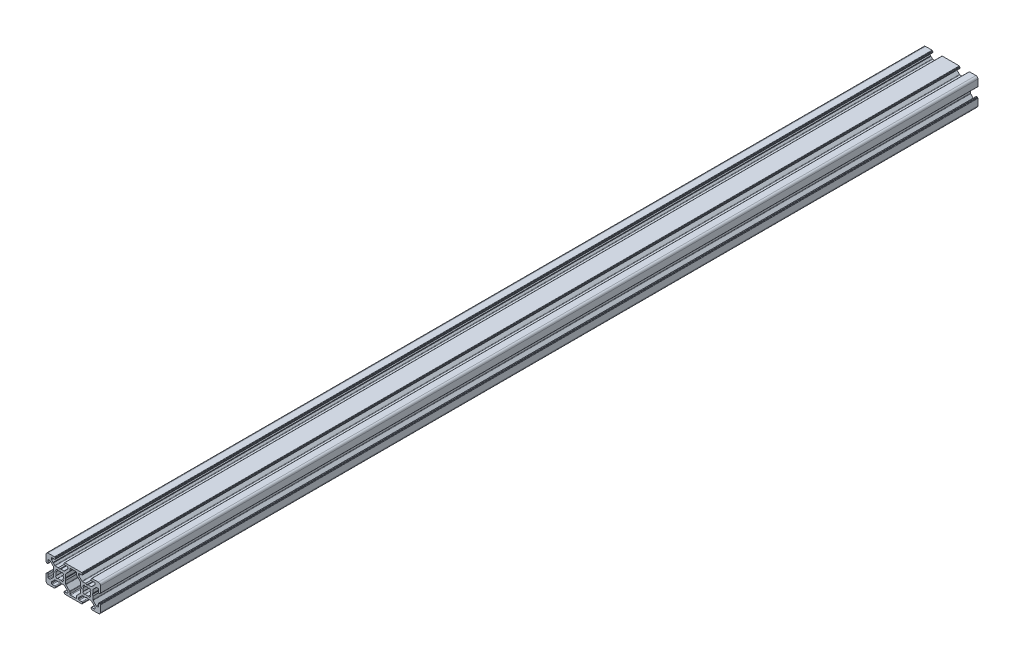
SolidWorks part; units mm, degrees
material "3.1355 (EN-AW 2024)"
ref_plane "Спереди" through (0, 0, 0) normal (0, 0, 1) x (1, 0, 0)
ref_plane "Сверху" through (0, 0, 0) normal (0, 1, 0) x (1, 0, 0)
ref_plane "Справа" through (0, 0, 0) normal (1, 0, 0) x (0, 0, -1)
sketch "Model" plane through (0, 0, 0) normal (0, 0, 1) x (1, 0, 0)
  line L0 (8.0901, 2.9922) -> (8.7418, 2.4453)
  line L1 (11.2582, 2.4453) -> (11.9099, 2.9922)
  line L2 (12.9896, 1.9139) -> (12.4453, 1.2582)
  line L3 (12.4453, -1.2582) -> (12.9896, -1.9139)
  line L4 (11.9099, -2.9922) -> (11.2582, -2.4453)
  line L5 (8.7418, -2.4453) -> (8.0901, -2.9922)
  line L6 (7.0104, -1.9139) -> (7.5547, -1.2582)
  line L7 (7.5547, 1.2582) -> (7.0104, 1.9139)
  line L8 (-7.0104, 1.9139) -> (-7.5547, 1.2582)
  line L9 (-7.5547, -1.2582) -> (-7.0104, -1.9139)
  line L10 (-8.0901, -2.9922) -> (-8.7418, -2.4453)
  line L11 (-11.2582, -2.4453) -> (-11.9099, -2.9922)
  line L12 (-12.9896, -1.9139) -> (-12.4453, -1.2582)
  line L13 (-12.4453, 1.2582) -> (-12.9896, 1.9139)
  line L14 (-11.9099, 2.9922) -> (-11.2582, 2.4453)
  line L15 (-8.7418, 2.4453) -> (-8.0901, 2.9922)
  line L16 (5.5267, 0.8538) -> (5.9619, 0.1)
  line L17 (5.9619, -0.1) -> (5.5267, -0.8538)
  line L18 (5.4999, -0.9538) -> (5.4999, -3.2324)
  line L19 (5.3534, -3.586) -> (2.6465, -6.2929)
  line L20 (2.5, -6.6464) -> (2.5, -8)
  line L21 (2, -8.5) -> (-2, -8.5)
  line L22 (-2.5, -8) -> (-2.5, -6.6464)
  line L23 (-2.6464, -6.2929) -> (-5.3535, -3.5858)
  line L24 (-5.5, -3.2322) -> (-5.5, -0.9536)
  line L25 (-5.5268, -0.8536) -> (-5.9619, -0.1)
  line L26 (-5.9619, 0.1) -> (-5.5268, 0.8536)
  line L27 (-5.5, 0.9536) -> (-5.5, 3.2322)
  line L28 (-5.3535, 3.5858) -> (-2.6464, 6.2929)
  line L29 (-2.5, 6.6464) -> (-2.5, 8)
  line L30 (-2, 8.5) -> (2, 8.5)
  line L31 (2.5, 8) -> (2.5, 6.6464)
  line L32 (2.6465, 6.2929) -> (5.3534, 3.586)
  line L33 (5.4999, 3.2324) -> (5.4999, 0.9538)
  line L34 (-14.7904, 5.7096) -> (-14.8421, 5.9028)
  line L35 (-14.8421, 5.9028) -> (-15.8536, 6.9142)
  line L36 (-16, 7.2678) -> (-16, 8)
  line L37 (-15.5, 8.5) -> (-13.6, 8.5)
  line L38 (-13.1, 9) -> (-13.1, 9.3)
  line L39 (-13.3, 9.5) -> (-13.35, 9.5)
  line L40 (-13.55, 9.7) -> (-13.55, 9.8)
  line L41 (-13.75, 10) -> (-18.5, 10)
  line L42 (-20, 8.5) -> (-20, 3.75)
  line L43 (-19.8, 3.55) -> (-19.7, 3.55)
  line L44 (-19.5, 3.35) -> (-19.5, 3.3)
  line L45 (-19.3, 3.1) -> (-19, 3.1)
  line L46 (-18.5, 3.6) -> (-18.5, 5.5)
  line L47 (-18, 6) -> (-17.2678, 6)
  line L48 (-16.9142, 5.8536) -> (-14.6464, 3.5858)
  line L49 (-14.5, 3.2322) -> (-14.5, 0.9536)
  line L50 (-14.4732, 0.8536) -> (-14.0381, 0.1)
  line L51 (-14.0381, -0.1) -> (-14.4732, -0.8536)
  line L52 (-14.5, -0.9536) -> (-14.5, -3.2322)
  line L53 (-14.6464, -3.5858) -> (-16.9142, -5.8536)
  line L54 (-17.2678, -6) -> (-18, -6)
  line L55 (-18.5, -5.5) -> (-18.5, -3.6)
  line L56 (-19, -3.1) -> (-19.3, -3.1)
  line L57 (-19.5, -3.3) -> (-19.5, -3.35)
  line L58 (-19.7, -3.55) -> (-19.8, -3.55)
  line L59 (-20, -3.75) -> (-20, -8.5)
  line L60 (-18.5, -10) -> (-13.75, -10)
  line L61 (-13.55, -9.8) -> (-13.55, -9.7)
  line L62 (-13.35, -9.5) -> (-13.3, -9.5)
  line L63 (-13.1, -9.3) -> (-13.1, -9)
  line L64 (-13.6, -8.5) -> (-15.5, -8.5)
  line L65 (-16, -8) -> (-16, -7.2678)
  line L66 (-15.8536, -6.9142) -> (-13.5858, -4.6464)
  line L67 (-13.2322, -4.5) -> (-10.9536, -4.5)
  line L68 (-10.8536, -4.4732) -> (-10.1, -4.0381)
  line L69 (-9.9, -4.0381) -> (-9.1464, -4.4732)
  line L70 (-9.0464, -4.5) -> (-6.7678, -4.5)
  line L71 (-6.4142, -4.6464) -> (-4.1464, -6.9142)
  line L72 (-4, -7.2678) -> (-4, -8)
  line L73 (-4.5, -8.5) -> (-6.4, -8.5)
  line L74 (-6.9, -9) -> (-6.9, -9.3)
  line L75 (-6.7, -9.5) -> (-6.65, -9.5)
  line L76 (-6.45, -9.7) -> (-6.45, -9.8)
  line L77 (-6.25, -10) -> (6.25, -10)
  line L78 (6.45, -9.8) -> (6.45, -9.7)
  line L79 (6.65, -9.5) -> (6.7, -9.5)
  line L80 (6.9, -9.3) -> (6.9, -9)
  line L81 (6.4, -8.5) -> (4.5, -8.5)
  line L82 (4, -8) -> (4, -7.2678)
  line L83 (4.1464, -6.9142) -> (6.4142, -4.6464)
  line L84 (6.7678, -4.5) -> (9.0464, -4.5)
  line L85 (9.1464, -4.4732) -> (9.9, -4.0381)
  line L86 (10.1, -4.0381) -> (10.8536, -4.4732)
  line L87 (10.9536, -4.5) -> (13.2322, -4.5)
  line L88 (13.5858, -4.6464) -> (15.8536, -6.9142)
  line L89 (16, -7.2678) -> (16, -8)
  line L90 (15.5, -8.5) -> (13.6, -8.5)
  line L91 (13.1, -9) -> (13.1, -9.3)
  line L92 (13.3, -9.5) -> (13.35, -9.5)
  line L93 (13.55, -9.7) -> (13.55, -9.8)
  line L94 (13.75, -10) -> (18.5, -10)
  line L95 (20, -8.5) -> (20, -3.75)
  line L96 (19.8, -3.55) -> (19.7, -3.55)
  line L97 (19.5, -3.35) -> (19.5, -3.3)
  line L98 (19.3, -3.1) -> (19, -3.1)
  line L99 (18.5, -3.6) -> (18.5, -5.5)
  line L100 (18, -6) -> (17.2678, -6)
  line L101 (16.9142, -5.8536) -> (14.6464, -3.5858)
  line L102 (14.5, -3.2322) -> (14.5, -0.9536)
  line L103 (14.4732, -0.8536) -> (14.0381, -0.1)
  line L104 (14.0381, 0.1) -> (14.4732, 0.8536)
  line L105 (14.5, 0.9536) -> (14.5, 3.2322)
  line L106 (14.6464, 3.5858) -> (16.9142, 5.8536)
  line L107 (17.2678, 6) -> (18, 6)
  line L108 (18.5, 5.5) -> (18.5, 3.6)
  line L109 (19, 3.1) -> (19.3, 3.1)
  line L110 (19.5, 3.3) -> (19.5, 3.35)
  line L111 (19.7, 3.55) -> (19.8, 3.55)
  line L112 (20, 3.75) -> (20, 8.5)
  line L113 (18.5, 10) -> (13.75, 10)
  line L114 (13.55, 9.8) -> (13.55, 9.7)
  line L115 (13.35, 9.5) -> (13.3, 9.5)
  line L116 (13.1, 9.3) -> (13.1, 9)
  line L117 (13.6, 8.5) -> (15.5, 8.5)
  line L118 (16, 8) -> (16, 7.2678)
  line L119 (15.8536, 6.9142) -> (13.5858, 4.6464)
  line L120 (13.2322, 4.5) -> (10.9536, 4.5)
  line L121 (10.8536, 4.4732) -> (10.1, 4.0381)
  line L122 (9.9, 4.0381) -> (9.1464, 4.4732)
  line L123 (9.0464, 4.5) -> (6.7678, 4.5)
  line L124 (6.4142, 4.6464) -> (4.1464, 6.9142)
  line L125 (4, 7.2678) -> (4, 8)
  line L126 (4.5, 8.5) -> (6.4, 8.5)
  line L127 (6.9, 9) -> (6.9, 9.3)
  line L128 (6.7, 9.5) -> (6.65, 9.5)
  line L129 (6.45, 9.7) -> (6.45, 9.8)
  line L130 (6.25, 10) -> (-6.25, 10)
  line L131 (-6.45, 9.8) -> (-6.45, 9.7)
  line L132 (-6.65, 9.5) -> (-6.7, 9.5)
  line L133 (-6.9, 9.3) -> (-6.9, 9)
  line L134 (-6.4, 8.5) -> (-4.5, 8.5)
  line L135 (-4, 8) -> (-4, 7.2678)
  line L136 (-4.1464, 6.9142) -> (-6.4142, 4.6464)
  line L137 (-6.7678, 4.5) -> (-9.0464, 4.5)
  line L138 (-9.1464, 4.4732) -> (-9.9, 4.0381)
  line L139 (-10.1, 4.0381) -> (-10.8536, 4.4732)
  line L140 (-10.9536, 4.5) -> (-13.2322, 4.5)
  line L141 (-13.5858, 4.6464) -> (-14.5972, 5.6579)
  line L142 (-14.5972, 5.6579) -> (-14.7904, 5.7096)
  arc A0 (8.0901, 2.9922) -> (7.0104, 1.9139) centre (10, 0) ccw
  arc A1 (11.2582, 2.4453) -> (8.7418, 2.4453) centre (10, 0) ccw
  arc A2 (12.9896, 1.9139) -> (11.9099, 2.9922) centre (10, 0) ccw
  arc A3 (12.4453, -1.2582) -> (12.4453, 1.2582) centre (10, 0) ccw
  arc A4 (11.9099, -2.9922) -> (12.9896, -1.9139) centre (10, 0) ccw
  arc A5 (8.7418, -2.4453) -> (11.2582, -2.4453) centre (10, 0) ccw
  arc A6 (7.0104, -1.9139) -> (8.0901, -2.9922) centre (10, 0) ccw
  arc A7 (7.5547, 1.2582) -> (7.5547, -1.2582) centre (10, 0) ccw
  arc A8 (-7.0104, 1.9139) -> (-8.0901, 2.9922) centre (-10, 0) ccw
  arc A9 (-7.5547, -1.2582) -> (-7.5547, 1.2582) centre (-10, 0) ccw
  arc A10 (-8.0901, -2.9922) -> (-7.0104, -1.9139) centre (-10, 0) ccw
  arc A11 (-11.2582, -2.4453) -> (-8.7418, -2.4453) centre (-10, 0) ccw
  arc A12 (-12.9896, -1.9139) -> (-11.9099, -2.9922) centre (-10, 0) ccw
  arc A13 (-12.4453, 1.2582) -> (-12.4453, -1.2582) centre (-10, 0) ccw
  arc A14 (-11.9099, 2.9922) -> (-12.9896, 1.9139) centre (-10, 0) ccw
  arc A15 (-8.7418, 2.4453) -> (-11.2582, 2.4453) centre (-10, 0) ccw
  arc A16 (5.9619, -0.1) -> (5.9619, 0.1) centre (5.7887, 0) ccw
  arc A17 (5.5267, -0.8538) -> (5.4999, -0.9538) centre (5.6999, -0.9538) ccw
  arc A18 (5.3534, -3.586) -> (5.4999, -3.2324) centre (4.9999, -3.2324) ccw
  arc A19 (2.6465, -6.2929) -> (2.5, -6.6464) centre (3, -6.6464) ccw
  arc A20 (2, -8.5) -> (2.5, -8) centre (2, -8) ccw
  arc A21 (-2.5, -8) -> (-2, -8.5) centre (-2, -8) ccw
  arc A22 (-2.5, -6.6464) -> (-2.6464, -6.2929) centre (-3, -6.6464) ccw
  arc A23 (-5.5, -3.2322) -> (-5.3535, -3.5858) centre (-5, -3.2322) ccw
  arc A24 (-5.5, -0.9536) -> (-5.5268, -0.8536) centre (-5.7, -0.9536) ccw
  arc A25 (-5.9619, 0.1) -> (-5.9619, -0.1) centre (-5.7887, 0) ccw
  arc A26 (-5.5268, 0.8536) -> (-5.5, 0.9536) centre (-5.7, 0.9536) ccw
  arc A27 (-5.3535, 3.5858) -> (-5.5, 3.2322) centre (-5, 3.2322) ccw
  arc A28 (-2.6464, 6.2929) -> (-2.5, 6.6464) centre (-3, 6.6464) ccw
  arc A29 (-2, 8.5) -> (-2.5, 8) centre (-2, 8) ccw
  arc A30 (2.5, 8) -> (2, 8.5) centre (2, 8) ccw
  arc A31 (2.5, 6.6464) -> (2.6465, 6.2929) centre (3, 6.6464) ccw
  arc A32 (5.4999, 3.2324) -> (5.3534, 3.586) centre (4.9999, 3.2324) ccw
  arc A33 (5.4999, 0.9538) -> (5.5267, 0.8538) centre (5.6999, 0.9538) ccw
  arc A34 (-16, 7.2678) -> (-15.8536, 6.9142) centre (-15.5, 7.2678) ccw
  arc A35 (-15.5, 8.5) -> (-16, 8) centre (-15.5, 8) ccw
  arc A36 (-13.6, 8.5) -> (-13.1, 9) centre (-13.6, 9) ccw
  arc A37 (-13.1, 9.3) -> (-13.3, 9.5) centre (-13.3, 9.3) ccw
  arc A38 (-13.55, 9.7) -> (-13.35, 9.5) centre (-13.35, 9.7) ccw
  arc A39 (-13.55, 9.8) -> (-13.75, 10) centre (-13.75, 9.8) ccw
  arc A40 (-18.5, 10) -> (-20, 8.5) centre (-18.5, 8.5) ccw
  arc A41 (-20, 3.75) -> (-19.8, 3.55) centre (-19.8, 3.75) ccw
  arc A42 (-19.5, 3.35) -> (-19.7, 3.55) centre (-19.7, 3.35) ccw
  arc A43 (-19.5, 3.3) -> (-19.3, 3.1) centre (-19.3, 3.3) ccw
  arc A44 (-19, 3.1) -> (-18.5, 3.6) centre (-19, 3.6) ccw
  arc A45 (-18, 6) -> (-18.5, 5.5) centre (-18, 5.5) ccw
  arc A46 (-16.9142, 5.8536) -> (-17.2678, 6) centre (-17.2678, 5.5) ccw
  arc A47 (-14.5, 3.2322) -> (-14.6464, 3.5858) centre (-15, 3.2322) ccw
  arc A48 (-14.5, 0.9536) -> (-14.4732, 0.8536) centre (-14.3, 0.9536) ccw
  arc A49 (-14.0381, -0.1) -> (-14.0381, 0.1) centre (-14.2113, 0) ccw
  arc A50 (-14.4732, -0.8536) -> (-14.5, -0.9536) centre (-14.3, -0.9536) ccw
  arc A51 (-14.6464, -3.5858) -> (-14.5, -3.2322) centre (-15, -3.2322) ccw
  arc A52 (-17.2678, -6) -> (-16.9142, -5.8536) centre (-17.2678, -5.5) ccw
  arc A53 (-18.5, -5.5) -> (-18, -6) centre (-18, -5.5) ccw
  arc A54 (-18.5, -3.6) -> (-19, -3.1) centre (-19, -3.6) ccw
  arc A55 (-19.3, -3.1) -> (-19.5, -3.3) centre (-19.3, -3.3) ccw
  arc A56 (-19.7, -3.55) -> (-19.5, -3.35) centre (-19.7, -3.35) ccw
  arc A57 (-19.8, -3.55) -> (-20, -3.75) centre (-19.8, -3.75) ccw
  arc A58 (-20, -8.5) -> (-18.5, -10) centre (-18.5, -8.5) ccw
  arc A59 (-13.75, -10) -> (-13.55, -9.8) centre (-13.75, -9.8) ccw
  arc A60 (-13.35, -9.5) -> (-13.55, -9.7) centre (-13.35, -9.7) ccw
  arc A61 (-13.3, -9.5) -> (-13.1, -9.3) centre (-13.3, -9.3) ccw
  arc A62 (-13.1, -9) -> (-13.6, -8.5) centre (-13.6, -9) ccw
  arc A63 (-16, -8) -> (-15.5, -8.5) centre (-15.5, -8) ccw
  arc A64 (-15.8536, -6.9142) -> (-16, -7.2678) centre (-15.5, -7.2678) ccw
  arc A65 (-13.2322, -4.5) -> (-13.5858, -4.6464) centre (-13.2322, -5) ccw
  arc A66 (-10.9536, -4.5) -> (-10.8536, -4.4732) centre (-10.9536, -4.3) ccw
  arc A67 (-9.9, -4.0381) -> (-10.1, -4.0381) centre (-10, -4.2113) ccw
  arc A68 (-9.1464, -4.4732) -> (-9.0464, -4.5) centre (-9.0464, -4.3) ccw
  arc A69 (-6.4142, -4.6464) -> (-6.7678, -4.5) centre (-6.7678, -5) ccw
  arc A70 (-4, -7.2678) -> (-4.1464, -6.9142) centre (-4.5, -7.2678) ccw
  arc A71 (-4.5, -8.5) -> (-4, -8) centre (-4.5, -8) ccw
  arc A72 (-6.4, -8.5) -> (-6.9, -9) centre (-6.4, -9) ccw
  arc A73 (-6.9, -9.3) -> (-6.7, -9.5) centre (-6.7, -9.3) ccw
  arc A74 (-6.45, -9.7) -> (-6.65, -9.5) centre (-6.65, -9.7) ccw
  arc A75 (-6.45, -9.8) -> (-6.25, -10) centre (-6.25, -9.8) ccw
  arc A76 (6.25, -10) -> (6.45, -9.8) centre (6.25, -9.8) ccw
  arc A77 (6.65, -9.5) -> (6.45, -9.7) centre (6.65, -9.7) ccw
  arc A78 (6.7, -9.5) -> (6.9, -9.3) centre (6.7, -9.3) ccw
  arc A79 (6.9, -9) -> (6.4, -8.5) centre (6.4, -9) ccw
  arc A80 (4, -8) -> (4.5, -8.5) centre (4.5, -8) ccw
  arc A81 (4.1464, -6.9142) -> (4, -7.2678) centre (4.5, -7.2678) ccw
  arc A82 (6.7678, -4.5) -> (6.4142, -4.6464) centre (6.7678, -5) ccw
  arc A83 (9.0464, -4.5) -> (9.1464, -4.4732) centre (9.0464, -4.3) ccw
  arc A84 (10.1, -4.0381) -> (9.9, -4.0381) centre (10, -4.2113) ccw
  arc A85 (10.8536, -4.4732) -> (10.9536, -4.5) centre (10.9536, -4.3) ccw
  arc A86 (13.5858, -4.6464) -> (13.2322, -4.5) centre (13.2322, -5) ccw
  arc A87 (16, -7.2678) -> (15.8536, -6.9142) centre (15.5, -7.2678) ccw
  arc A88 (15.5, -8.5) -> (16, -8) centre (15.5, -8) ccw
  arc A89 (13.6, -8.5) -> (13.1, -9) centre (13.6, -9) ccw
  arc A90 (13.1, -9.3) -> (13.3, -9.5) centre (13.3, -9.3) ccw
  arc A91 (13.55, -9.7) -> (13.35, -9.5) centre (13.35, -9.7) ccw
  arc A92 (13.55, -9.8) -> (13.75, -10) centre (13.75, -9.8) ccw
  arc A93 (18.5, -10) -> (20, -8.5) centre (18.5, -8.5) ccw
  arc A94 (20, -3.75) -> (19.8, -3.55) centre (19.8, -3.75) ccw
  arc A95 (19.5, -3.35) -> (19.7, -3.55) centre (19.7, -3.35) ccw
  arc A96 (19.5, -3.3) -> (19.3, -3.1) centre (19.3, -3.3) ccw
  arc A97 (19, -3.1) -> (18.5, -3.6) centre (19, -3.6) ccw
  arc A98 (18, -6) -> (18.5, -5.5) centre (18, -5.5) ccw
  arc A99 (16.9142, -5.8536) -> (17.2678, -6) centre (17.2678, -5.5) ccw
  arc A100 (14.5, -3.2322) -> (14.6464, -3.5858) centre (15, -3.2322) ccw
  arc A101 (14.5, -0.9536) -> (14.4732, -0.8536) centre (14.3, -0.9536) ccw
  arc A102 (14.0381, 0.1) -> (14.0381, -0.1) centre (14.2113, 0) ccw
  arc A103 (14.4732, 0.8536) -> (14.5, 0.9536) centre (14.3, 0.9536) ccw
  arc A104 (14.6464, 3.5858) -> (14.5, 3.2322) centre (15, 3.2322) ccw
  arc A105 (17.2678, 6) -> (16.9142, 5.8536) centre (17.2678, 5.5) ccw
  arc A106 (18.5, 5.5) -> (18, 6) centre (18, 5.5) ccw
  arc A107 (18.5, 3.6) -> (19, 3.1) centre (19, 3.6) ccw
  arc A108 (19.3, 3.1) -> (19.5, 3.3) centre (19.3, 3.3) ccw
  arc A109 (19.7, 3.55) -> (19.5, 3.35) centre (19.7, 3.35) ccw
  arc A110 (19.8, 3.55) -> (20, 3.75) centre (19.8, 3.75) ccw
  arc A111 (20, 8.5) -> (18.5, 10) centre (18.5, 8.5) ccw
  arc A112 (13.75, 10) -> (13.55, 9.8) centre (13.75, 9.8) ccw
  arc A113 (13.35, 9.5) -> (13.55, 9.7) centre (13.35, 9.7) ccw
  arc A114 (13.3, 9.5) -> (13.1, 9.3) centre (13.3, 9.3) ccw
  arc A115 (13.1, 9) -> (13.6, 8.5) centre (13.6, 9) ccw
  arc A116 (16, 8) -> (15.5, 8.5) centre (15.5, 8) ccw
  arc A117 (15.8536, 6.9142) -> (16, 7.2678) centre (15.5, 7.2678) ccw
  arc A118 (13.2322, 4.5) -> (13.5858, 4.6464) centre (13.2322, 5) ccw
  arc A119 (10.9536, 4.5) -> (10.8536, 4.4732) centre (10.9536, 4.3) ccw
  arc A120 (9.9, 4.0381) -> (10.1, 4.0381) centre (10, 4.2113) ccw
  arc A121 (9.1464, 4.4732) -> (9.0464, 4.5) centre (9.0464, 4.3) ccw
  arc A122 (6.4142, 4.6464) -> (6.7678, 4.5) centre (6.7678, 5) ccw
  arc A123 (4, 7.2678) -> (4.1464, 6.9142) centre (4.5, 7.2678) ccw
  arc A124 (4.5, 8.5) -> (4, 8) centre (4.5, 8) ccw
  arc A125 (6.4, 8.5) -> (6.9, 9) centre (6.4, 9) ccw
  arc A126 (6.9, 9.3) -> (6.7, 9.5) centre (6.7, 9.3) ccw
  arc A127 (6.45, 9.7) -> (6.65, 9.5) centre (6.65, 9.7) ccw
  arc A128 (6.45, 9.8) -> (6.25, 10) centre (6.25, 9.8) ccw
  arc A129 (-6.25, 10) -> (-6.45, 9.8) centre (-6.25, 9.8) ccw
  arc A130 (-6.65, 9.5) -> (-6.45, 9.7) centre (-6.65, 9.7) ccw
  arc A131 (-6.7, 9.5) -> (-6.9, 9.3) centre (-6.7, 9.3) ccw
  arc A132 (-6.9, 9) -> (-6.4, 8.5) centre (-6.4, 9) ccw
  arc A133 (-4, 8) -> (-4.5, 8.5) centre (-4.5, 8) ccw
  arc A134 (-4.1464, 6.9142) -> (-4, 7.2678) centre (-4.5, 7.2678) ccw
  arc A135 (-6.7678, 4.5) -> (-6.4142, 4.6464) centre (-6.7678, 5) ccw
  arc A136 (-9.0464, 4.5) -> (-9.1464, 4.4732) centre (-9.0464, 4.3) ccw
  arc A137 (-10.1, 4.0381) -> (-9.9, 4.0381) centre (-10, 4.2113) ccw
  arc A138 (-10.8536, 4.4732) -> (-10.9536, 4.5) centre (-10.9536, 4.3) ccw
  arc A139 (-13.5858, 4.6464) -> (-13.2322, 4.5) centre (-13.2322, 5) ccw
  dimension "D1" = 20
extrude "База" add sketch "Model" along normal mid plane 645
